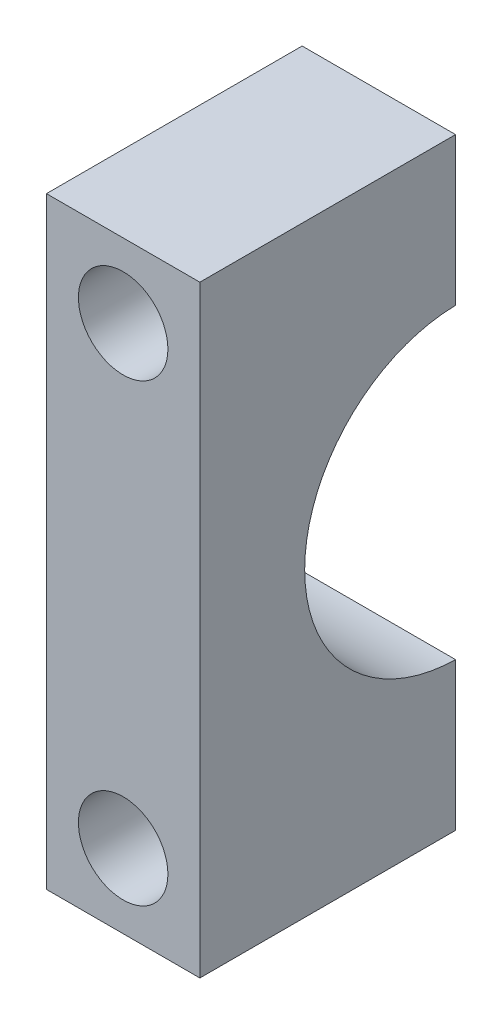
SolidWorks part; units mm, degrees
ref_plane "Přední rovina" through (0, 0, 0) normal (0, 0, 1) x (1, 0, 0)
ref_plane "Horní rovina" through (0, 0, 0) normal (0, 1, 0) x (1, 0, 0)
ref_plane "Pravá rovina" through (0, 0, 0) normal (1, 0, 0) x (0, 0, -1)
sketch "Skica1" plane through (0, 0, 0) normal (0, 0, 1) x (1, 0, 0)
  line L1 (25.816, 2.4921) -> (25.816, 8.2771) construction
  line L2 (25.816, 8.2771) -> (19.816, 8.2771) construction
  line L3 (19.816, 8.2771) -> (19.816, 2.4921) construction
  line L5 (19.816, -9.5062) -> (19.816, -15.2912) construction
  line L6 (19.816, -15.2912) -> (25.816, -15.2912) construction
  line L7 (25.816, -15.2912) -> (25.816, -9.5062) construction
  line L9 (25.816, 2.4921) -> (25.816, 8.2771)
  line L10 (25.816, 8.2771) -> (19.816, 8.2771)
  line L11 (19.816, 8.2771) -> (19.816, 2.4921)
  line L13 (19.816, -9.5062) -> (19.816, -15.2912)
  line L14 (19.816, -15.2912) -> (25.816, -15.2912)
  line L15 (25.816, -15.2912) -> (25.816, -9.5062)
  line L18 (19.816, -9.5062) -> (19.816, 2.4921)
  line L20 (25.816, -9.5062) -> (25.816, 2.4921)
  circle A0 centre (22.816, -12.3987) radius 1.75
  circle A1 centre (22.816, 5.3846) radius 1.75
  dimension "D1" = 3.5
extrude "Přidat vysunutím1" add sketch "Skica1" along normal blind 10
sketch "Skica2" plane through (19.816, 0, 0) normal (-1, 0, 0) x (0, 0, 1)
  circle A0 centre (-0.0997, -3.507) radius 6
extrude "Odebrat vysunutím1" cut sketch "Skica2" against normal blind 6
